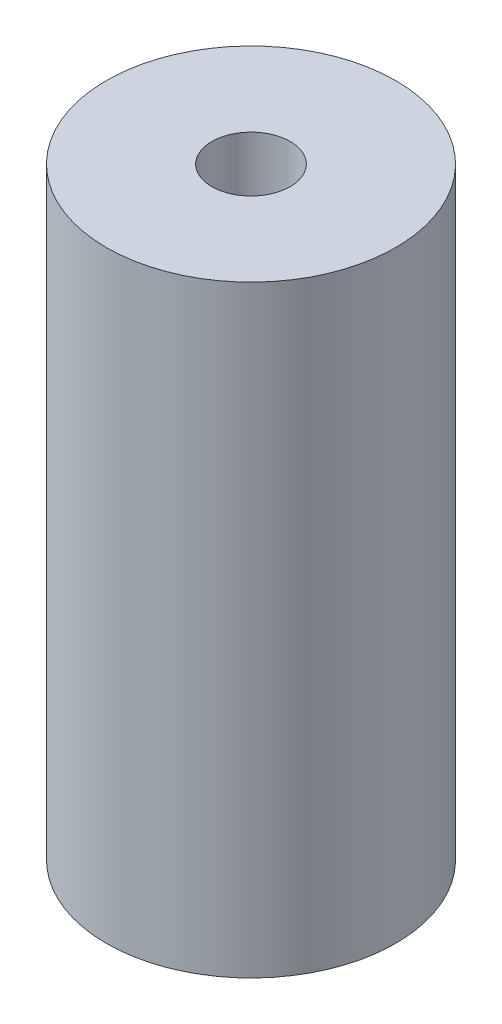
SolidWorks part; units mm, degrees
ref_plane "Front Plane" through (0, 0, 0) normal (0, 0, 1) x (1, 0, 0)
ref_plane "Top Plane" through (0, 0, 0) normal (0, 1, 0) x (1, 0, 0)
ref_plane "Right Plane" through (0, 0, 0) normal (1, 0, 0) x (0, 0, -1)
sketch "Sketch1" plane through (0, 0, 0) normal (0, 1, 0) x (1, 0, 0)
  circle A0 centre (0, 0) radius 3.25
  circle A1 centre (0, 0) radius 12
  dimension "D1" = 6.5
  dimension "D2" = 24
extrude "Boss-Extrude1" add sketch "Sketch1" along normal mid plane 50
